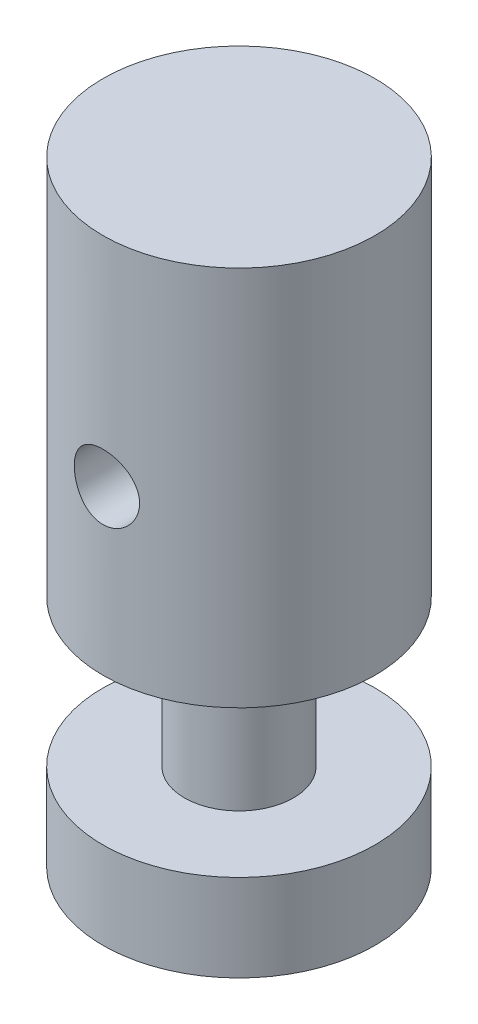
SolidWorks part; units mm, degrees
ref_plane "Front Plane" through (0, 0, 0) normal (0, 0, 1) x (1, 0, 0)
ref_plane "Top Plane" through (0, 0, 0) normal (0, 1, 0) x (1, 0, 0)
ref_plane "Right Plane" through (0, 0, 0) normal (1, 0, 0) x (0, 0, -1)
sketch "Sketch1" plane through (0, 0, 0) normal (0, 1, 0) x (1, 0, 0)
  circle A0 centre (0, 0) radius 2.5
  dimension "D1" = 5
extrude "Boss-Extrude1" add sketch "Sketch1" along normal blind 7
sketch "Sketch2" plane through (0, 0, 0) normal (0, 0, 1) x (1, 0, 0)
  line L0 (0, 0) -> (0, 3) construction
  line L1 (-2.5, 0) -> (2.5, 0) construction
  circle A0 centre (0, 3) radius 0.6
  dimension "D2" = 1.2
  dimension "D1" = 3
extrude "Cut-Extrude1" cut sketch "Sketch2" against normal through all both and the other way through all
sketch "Sketch3" plane through (0, 0, 0) normal (0, -1, 0) x (1, 0, 0)
  circle A0 centre (0, 0) radius 1.0027
  dimension "D1" = 2.0055
extrude "Boss-Extrude2" add sketch "Sketch3" along normal blind 4.3
sketch "Sketch4" plane through (0, -4.3, 0) normal (0, -1, 0) x (1, 0, 0)
  circle A0 centre (0, 0) radius 2.5 construction
  circle A1 centre (0, 0) radius 2.5
extrude "Boss-Extrude3" add sketch "Sketch4" against normal blind 1.6
